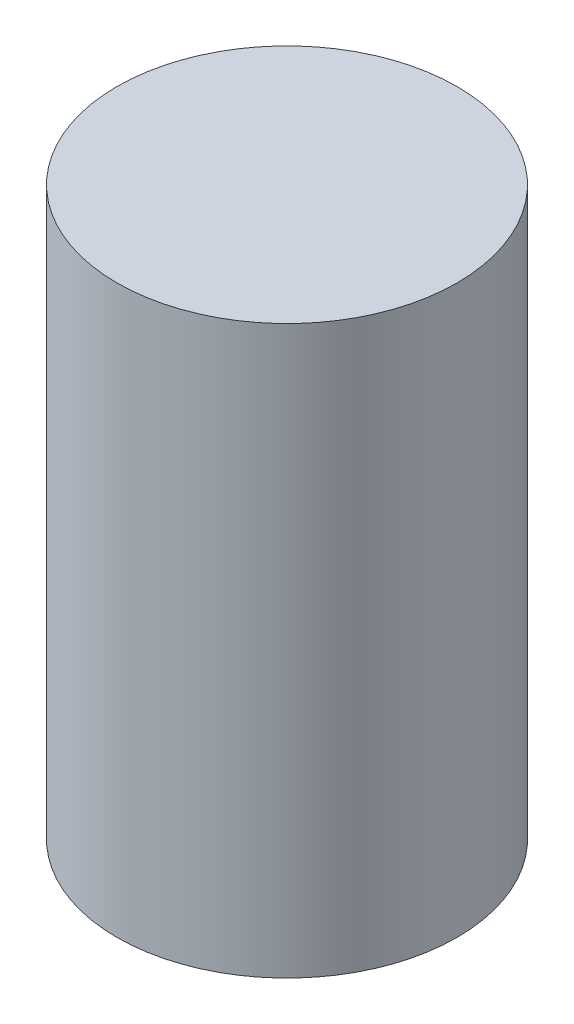
SolidWorks part; units mm, degrees
ref_plane "Alzado" through (0, 0, 0) normal (0, 0, 1) x (1, 0, 0)
ref_plane "Planta" through (0, 0, 0) normal (0, 1, 0) x (1, 0, 0)
ref_plane "Vista lateral" through (0, 0, 0) normal (1, 0, 0) x (0, 0, -1)
sketch "Croquis_perfil" plane through (0, 0, 0) normal (0, 0, 1) x (1, 0, 0)
  line L0 (0, 0) -> (0, 100) construction
  line L1 (0, 0) -> (30, 0)
  line L2 (30, 0) -> (30, 100)
  line L3 (30, 100) -> (0, 100)
  line L4 (0, 100) -> (0, 0)
  dimension "D1" = 30
  dimension "D2" = 100
revolve "Cilindro_D60x100" add sketch "Croquis_perfil" angle 360 about L0
sketch "Croquis_agujeros_montaje" plane through (0, 0, 0) normal (0, 1, 0) x (1, 0, 0)
  circle A0 centre (0, 0) radius 4
  dimension "D1" = 8
extrude "Agujero_inserto_M6" cut sketch "Croquis_agujeros_montaje" along normal blind 14
